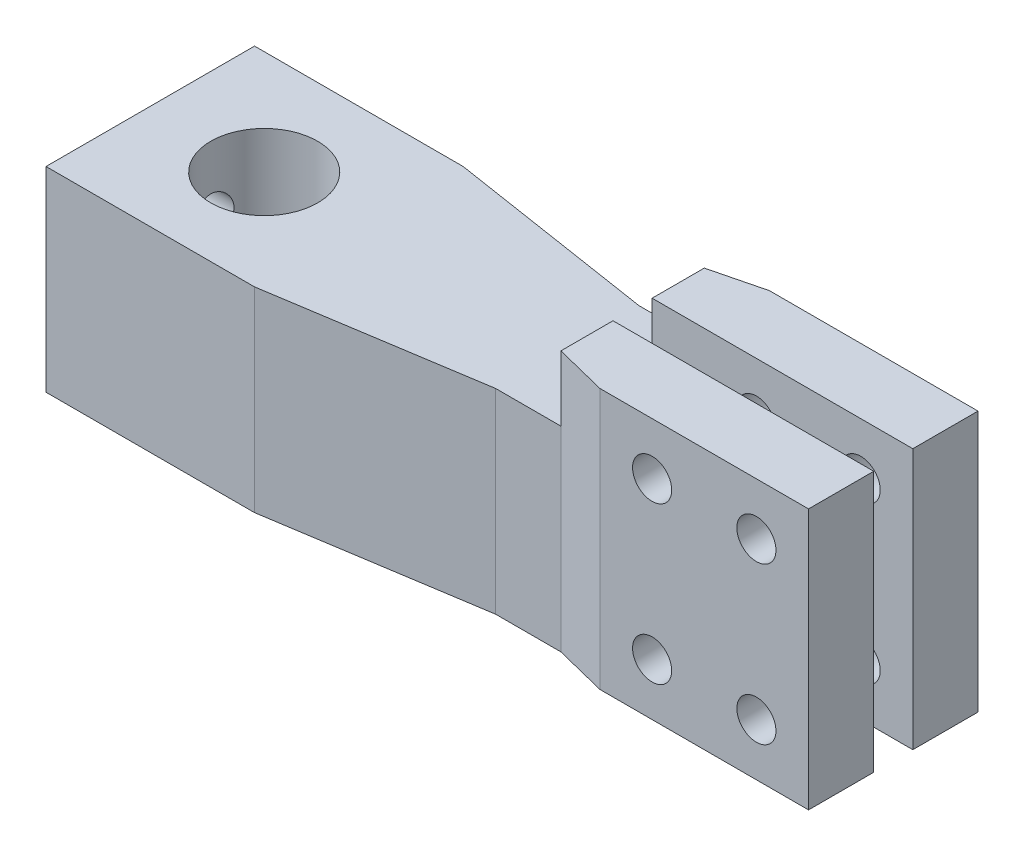
SolidWorks part; units mm, degrees
ref_plane "Front Plane" through (0, 0, 0) normal (0, 0, 1) x (1, 0, 0)
ref_plane "Top Plane" through (0, 0, 0) normal (0, 1, 0) x (1, 0, 0)
ref_plane "Right Plane" through (0, 0, 0) normal (1, 0, 0) x (0, 0, -1)
sketch "Sketch2" plane through (0, 0, 0) normal (0, 1, 0) x (1, 0, 0)
  line L0 (-16, -8) -> (-16, 8)
  line L1 (-8.25, 0) -> (8.25, 0) construction
  line L2 (-16, 8) -> (0, 8)
  line L3 (0, -8.25) -> (0, 8.25) construction
  line L4 (0, 8) -> (16, 5.5)
  line L5 (16, 5.5) -> (21, 5.5)
  line L6 (21, 5.5) -> (21, -5.5)
  line L8 (16, -5.5) -> (21, -5.5)
  line L9 (0, -8) -> (16, -5.5)
  line L10 (-16, -8) -> (0, -8)
  point P11 (21, 0)
  point P14 (-16, 0)
  dimension "D1" = 5.5
  dimension "D2" = 8
  dimension "D3" = 16
  dimension "D4" = 16
  dimension "D5" = 5
extrude "Boss-Extrude1" add sketch "Sketch2" along normal mid plane 15
sketch "Sketch4" plane through (0, 7.5, 0) normal (0, 1, 0) x (1, 0, 0)
  line L0 (-11, 0) -> (11, 0) construction
  circle A0 centre (-7.26, 0) radius 4.1
  dimension "D1" = 8.2
extrude "Cut-Extrude1" cut sketch "Sketch4" against normal blind 10
sketch "Sketch5" plane through (0, -2.5, 0) normal (0, 1, 0) x (1, 0, 0)
  circle A0 centre (-7.26, 0) radius 1.5
  dimension "D1" = 3
extrude "Cut-Extrude2" cut sketch "Sketch5" against normal up to surface (5 mm away) up to face at (5.25, -7.5, 0)
sketch "Sketch7" plane through (-16, 0, 0) normal (-1, 0, 0) x (0, 0, 1)
  line L0 (0, -11) -> (0, 11) construction
  line L2 (-8, 7.5) -> (8, 7.5) construction
  circle A0 centre (0, 2.5) radius 1.5
  dimension "D1" = 3
  dimension "D2" = 5
extrude "Cut-Extrude4" cut sketch "Sketch7" against normal up to surface (4.9243 mm away)
sketch "Sketch9" plane through (0, -7.5, 0) normal (0, 1, 0) x (1, 0, 0)
  line L0 (21, 5.5) -> (25, 6.5)
  line L1 (25, 6.5) -> (41, 6.5)
  line L2 (41, 6.5) -> (41, -6.5)
  line L3 (41, -6.5) -> (25, -6.5)
  line L4 (25, -6.5) -> (21, -5.5)
  line L5 (21, -5.5) -> (21, 5.5)
  line L6 (-11, 0) -> (11, 0) construction
  point P3 (41, 0)
  dimension "D1" = 13
  dimension "D2" = 20
  dimension "D3" = 16
  dimension "D4" = 16
extrude "Boss-Extrude2" add sketch "Sketch9" along normal blind 20
sketch "Sketch10" plane through (0, 12.5, 0) normal (0, 1, 0) x (1, 0, 0)
  line L0 (41, -6.5) -> (41, 6.5) construction
  line L1 (41, 1.5) -> (21, 1.5)
  line L2 (41, 1.5) -> (41, -1.5)
  line L3 (41, -1.5) -> (21, -1.5)
  line L4 (21, 1.5) -> (21, -1.5)
  line L5 (-11, 0) -> (11, 0) construction
  dimension "D1" = 3
  dimension "D2" = 20
  dimension "D3" = 1.5
extrude "Cut-Extrude5" cut sketch "Sketch10" against normal blind 20
sketch "Sketch11" plane through (0, 0, -6.5) normal (0, 0, -1) x (-1, 0, 0)
  line L0 (-41, 12.5) -> (-25, 12.5) construction
  line L1 (-41, 12.5) -> (-41, -7.5) construction
  line L2 (-25, 12.5) -> (-25, -7.5) construction
  circle A0 centre (-37, 8.5) radius 1.5
  circle A1 centre (-29, 8.5) radius 1.5
  circle A2 centre (-37, -3.5) radius 1.5
  circle A3 centre (-29, -3.5) radius 1.5
  dimension "D1" = 3
  dimension "D2" = 3
  dimension "D3" = 3
  dimension "D4" = 3
  dimension "D5" = 12
  dimension "D6" = 4
  dimension "D7" = 4
  dimension "D8" = 4
extrude "Cut-Extrude6" cut sketch "Sketch11" against normal through all and the other way through all
